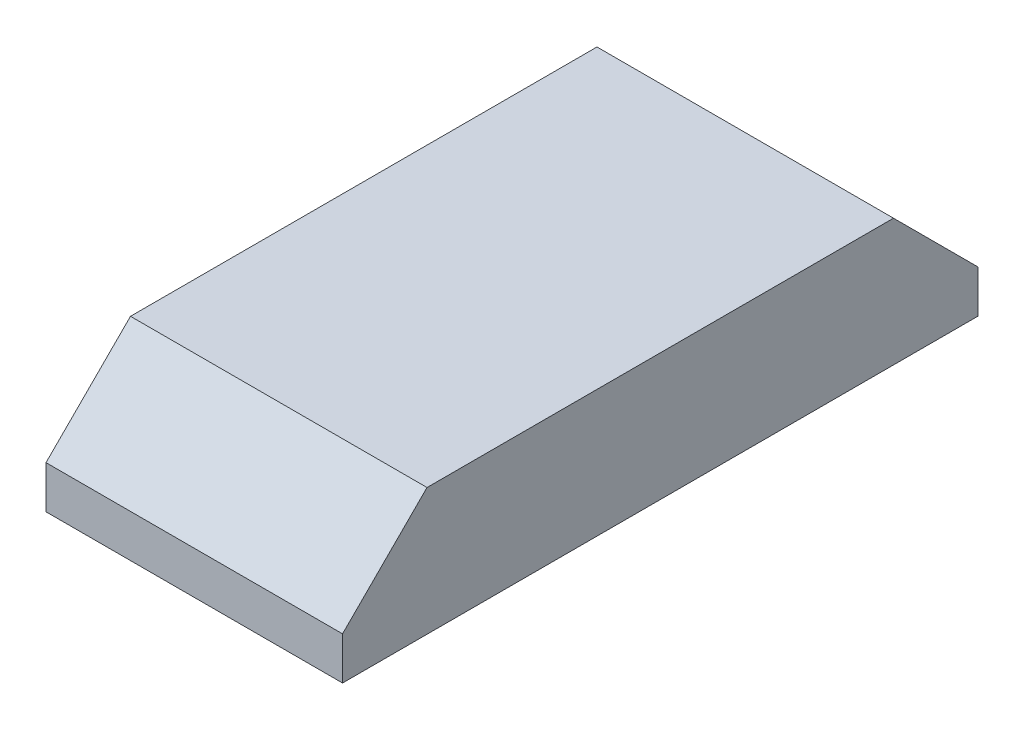
SolidWorks part; units mm, degrees
material "Pine"
ref_plane "Front Plane" through (0, 0, 0) normal (0, 0, 1) x (1, 0, 0)
ref_plane "Top Plane" through (0, 0, 0) normal (0, 1, 0) x (1, 0, 0)
ref_plane "Right Plane" through (0, 0, 0) normal (1, 0, 0) x (0, 0, -1)
sketch "Sketch1" plane through (0, 0, 0) normal (0, 1, 0) x (1, 0, 0)
  line L1 (0, 0) -> (88.9, 0)
  line L2 (0, 0) -> (0, -190.5)
  line L3 (0, -190.5) -> (88.9, -190.5)
  line L4 (88.9, 0) -> (88.9, -190.5)
  dimension "D1" = 190.5
  dimension "D2" = 88.9
extrude "Boss-Extrude1" add sketch "Sketch1" along normal blind 38.1
sketch "Sketch2" plane through (88.9, 0, 0) normal (1, 0, 0) x (0, 0, -1)
  line L0 (-190.5, 12.7728) -> (-190.5, 38.1)
  line L1 (0, 38.1) -> (0, 0) construction
  line L2 (-190.5, 38.1) -> (-165.1728, 38.1)
  line L3 (-190.5, 38.1) -> (-190.5, 0) construction
  line L4 (-190.5, 12.7728) -> (-165.1728, 38.1)
  line L5 (-190.5, 38.1) -> (0, 38.1) construction
  line L6 (0, 12.7728) -> (-25.3272, 38.1)
  line L7 (-25.3272, 38.1) -> (0, 38.1)
  line L8 (0, 38.1) -> (0, 12.7728)
extrude "Cut-Extrude2" cut sketch "Sketch2" against normal blind 88.9
